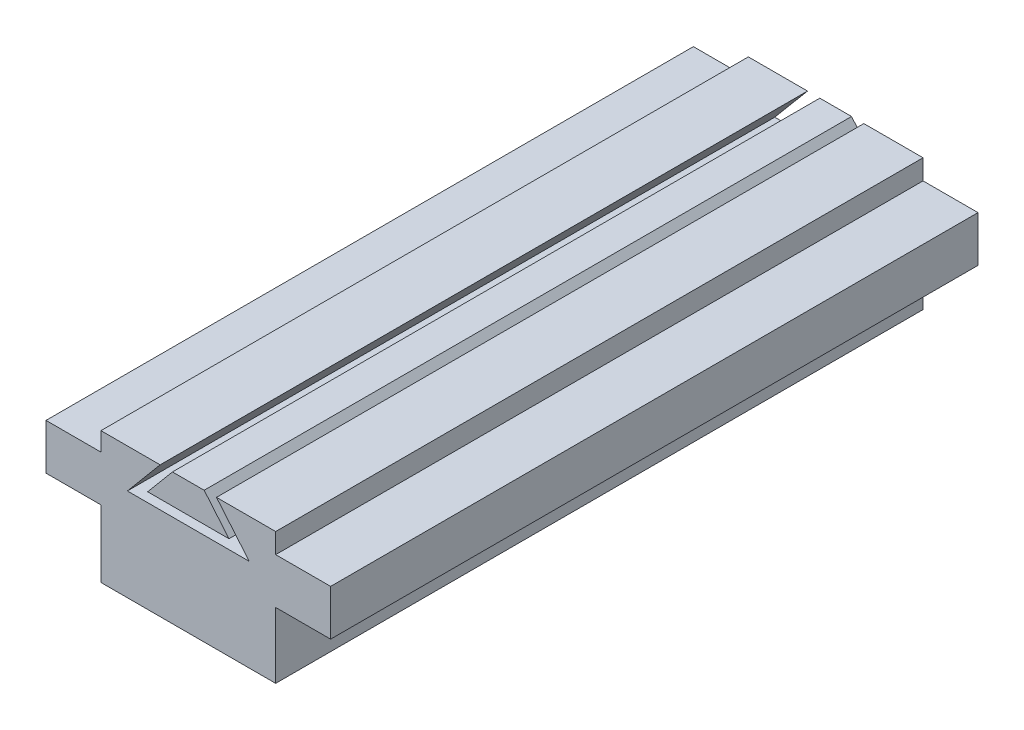
SolidWorks part; units mm, degrees
ref_plane "Front Plane" through (0, 0, 0) normal (0, 0, 1) x (1, 0, 0)
ref_plane "Top Plane" through (0, 0, 0) normal (0, 1, 0) x (1, 0, 0)
ref_plane "Right Plane" through (0, 0, 0) normal (1, 0, 0) x (0, 0, -1)
sketch "Sketch1" plane through (0, 0, 0) normal (0, 0, 1) x (1, 0, 0)
  line L0 (-0.4287, 0) -> (0.4287, 0)
  line L1 (0.4287, 0) -> (1.1, -0.8)
  line L2 (1.1, -0.8) -> (-1.1, -0.8)
  line L3 (-1.1, -0.8) -> (-0.4287, 0)
  point P3 (0, 0)
  dimension "D1" = 50
  dimension "D2" = 0.8
  dimension "D3" = 2.2
extrude "Boss-Extrude1" add sketch "Sketch1" along normal blind 17.5
sketch "Sketch4" plane through (0, 0, 17.5) normal (0, 0, 1) x (1, 0, 0)
  line L0 (-0.7616, 0) -> (-1.6468, -1.055)
  line L1 (-1.6468, -1.055) -> (1.6468, -1.055)
  line L2 (1.6468, -1.055) -> (0.7616, 0)
  line L3 (0.7616, 0) -> (2.3616, 0)
  line L4 (2.3616, 0) -> (2.3616, -3.555)
  line L5 (2.3616, -3.555) -> (-2.3616, -3.555)
  line L6 (-2.3616, -3.555) -> (-2.3616, 0)
  line L7 (-2.3616, 0) -> (-0.7616, 0)
  line L9 (-1.1, -0.8) -> (1.1, -0.8) construction
  line L11 (1.1, -0.8) -> (0.4287, 0) construction
  line L12 (-0.4287, 0) -> (-1.1, -0.8) construction
  dimension "D1" = 1.6
  dimension "D2" = 2.5
  dimension "D3" = 0.255
  dimension "D4" = 0.255
  dimension "D5" = 0.255
extrude "Boss-Extrude2" add sketch "Sketch4" against normal up to surface (17.5 mm away) separate body up to face at (0, -0.4, 0)
sketch "Sketch5" plane through (0, 0, 17.5) normal (0, 0, 1) x (1, 0, 0)
  line L0 (-2.3616, 0) -> (-2.3616, -3.555) construction
  line L1 (-2.3616, -0.5026) -> (-3.847, -0.5026)
  line L2 (-2.3616, -0.5026) -> (-2.3616, -1.7383)
  line L3 (-2.3616, -1.7383) -> (-3.847, -1.7383)
  line L4 (-3.847, -0.5026) -> (-3.847, -1.7383)
  line L5 (3.847, -0.5414) -> (2.3616, -0.5414)
  line L6 (3.847, -0.5414) -> (3.847, -1.777)
  line L7 (3.847, -1.777) -> (2.3616, -1.777)
  line L8 (2.3616, -0.5414) -> (2.3616, -1.777)
  line L9 (2.3616, -3.555) -> (2.3616, 0) construction
  dimension "D1" = 1.4854
  dimension "D2" = 1.2356
extrude "Boss-Extrude3" add sketch "Sketch5" against normal up to surface (17.5 mm away) up to face at (0, -1.1525, 0)
sketch "Sketch6" plane through (0, -3.555, 0) normal (0, -1, 0) x (1, 0, 0)
  line L0 (-2.3616, 17.5) -> (2.3616, 17.5) construction
  circle A0 centre (0, 16.087) radius 0.6771
  circle A1 centre (0, 12.277) radius 0.6771
  circle A2 centre (0, 8.467) radius 0.6771
  circle A3 centre (0, 4.657) radius 0.6771
  point P12 (0, 17.5)
  dimension "D1" = 3.81
  dimension "D2" = 3.81
  dimension "D3" = 3.81
extrude "Cut-Extrude1" cut sketch "Sketch6" against normal up to surface (2.5 mm away) up to face at (0, -1.055, 8.75)
equation "\"TOL\"= 0.255mm"
